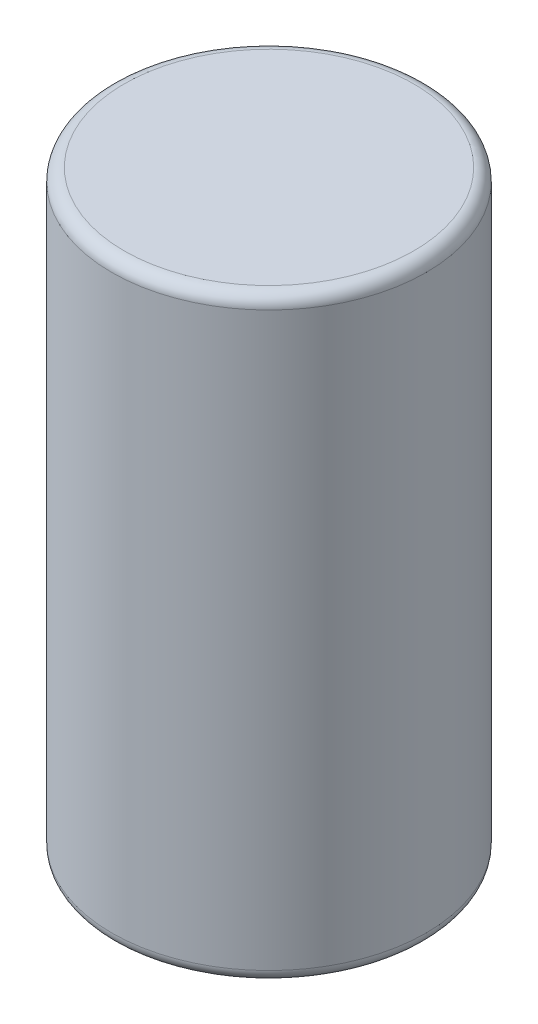
SolidWorks part; units mm, degrees
ref_plane "Front" through (0, 0, 0) normal (0, 0, 1) x (1, 0, 0)
ref_plane "Top" through (0, 0, 0) normal (0, 1, 0) x (1, 0, 0)
ref_plane "Right" through (0, 0, 0) normal (1, 0, 0) x (0, 0, -1)
sketch "Sketch1" plane through (0, 0, 0) normal (0, 1, 0) x (1, 0, 0)
  circle A0 centre (0, 0) radius 40.132
  dimension "D1" = 80.264
extrude "Boss-Extrude1" add sketch "Sketch1" along normal blind 152.4
fillet "Fillet1" radius 3.175 2 edges at (0, 0, 40.132) (0, 152.4, 40.132)
